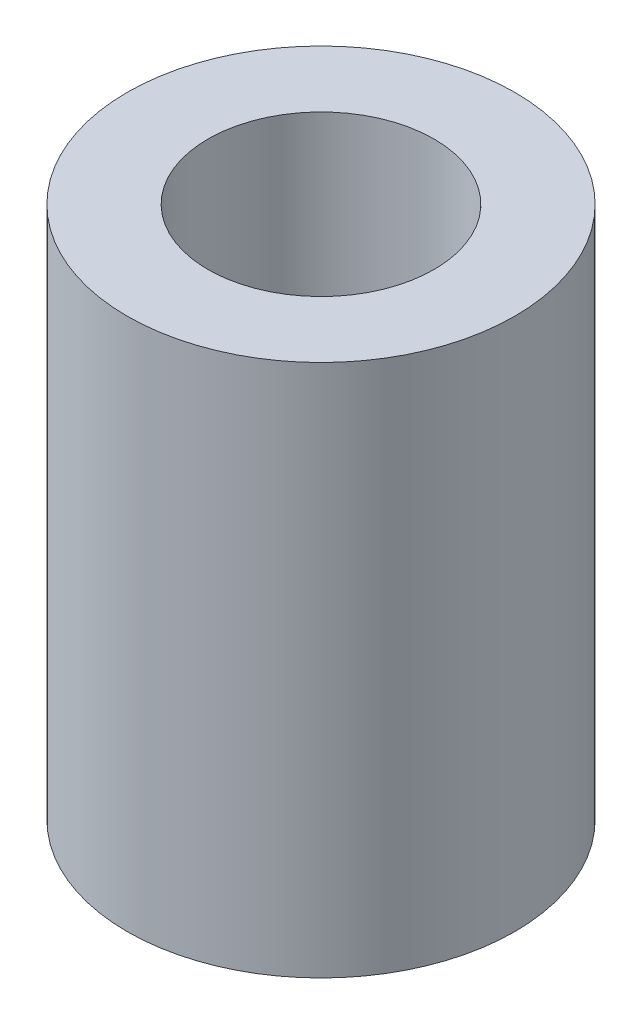
SolidWorks part; units mm, degrees
ref_plane "Front Plane" through (0, 0, 0) normal (0, 0, 1) x (1, 0, 0)
ref_plane "Top Plane" through (0, 0, 0) normal (0, 1, 0) x (1, 0, 0)
ref_plane "Right Plane" through (0, 0, 0) normal (1, 0, 0) x (0, 0, -1)
sketch "Sketch1" plane through (0, 0, 0) normal (0, 1, 0) x (1, 0, 0)
  circle A0 centre (0, 0) radius 2.1
  circle A1 centre (0, 0) radius 3.6
  dimension "D1" = 7.2
  dimension "D2" = 4.2
extrude "Boss-Extrude1" add sketch "Sketch1" along normal blind 9.9
